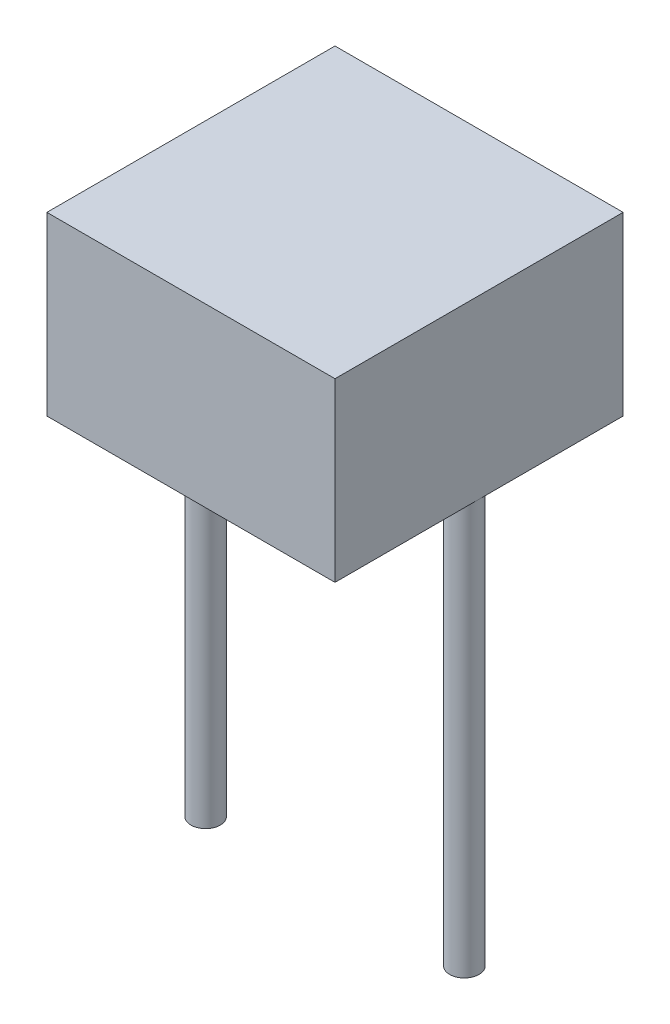
SolidWorks part; units mm, degrees
ref_plane "Front Plane" through (0, 0, 0) normal (0, 0, 1) x (1, 0, 0)
ref_plane "Top Plane" through (0, 0, 0) normal (0, 1, 0) x (1, 0, 0)
ref_plane "Right Plane" through (0, 0, 0) normal (1, 0, 0) x (0, 0, -1)
sketch "Sketch1" plane through (0, 0, 0) normal (0, 1, 0) x (1, 0, 0)
  line L1 (-3.1115, 3.1115) -> (3.1115, 3.1115)
  line L2 (-3.1115, 3.1115) -> (-3.1115, -3.1115)
  line L3 (-3.1115, -3.1115) -> (3.1115, -3.1115)
  line L4 (3.1115, 3.1115) -> (3.1115, -3.1115)
  line L5 (-3.1115, 3.1115) -> (3.1115, -3.1115) construction
  line L6 (-3.1115, -3.1115) -> (3.1115, 3.1115) construction
  point P0 (0, 0)
  dimension "D1" = 6.223
  dimension "D2" = 6.223
extrude "Boss-Extrude1" add sketch "Sketch1" along normal blind 3.81
sketch "Sketch2" plane through (0, 0, 0) normal (0, -1, 0) x (1, 0, 0)
  line L11 (-3.1115, -3.1115) -> (-3.1115, 3.1115) construction
  line L12 (-2.794, 0) -> (0, 0) construction
  line L13 (0, 0) -> (2.794, 0) construction
  line L14 (3.1115, 3.1115) -> (3.1115, -3.1115) construction
  circle A0 centre (-2.794, 0) radius 0.3175
  circle A1 centre (2.794, 0) radius 0.3175
  dimension "D1" = 0.635
  dimension "D2" = 0.635
extrude "Boss-Extrude2" add sketch "Sketch2" along normal blind 8.89
